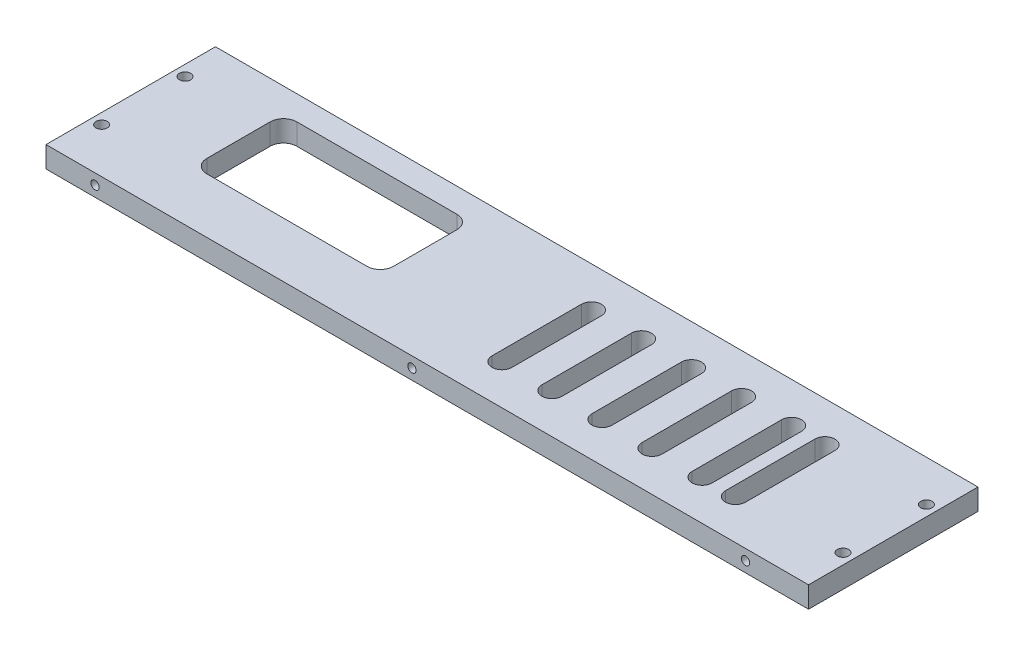
SolidWorks part; units mm, degrees
material "Aleación 6061"
ref_plane "Alzado" through (0, 0, 0) normal (0, 0, 1) x (1, 0, 0)
ref_plane "Planta" through (0, 0, 0) normal (0, 1, 0) x (1, 0, 0)
ref_plane "Vista lateral" through (0, 0, 0) normal (1, 0, 0) x (0, 0, -1)
sketch "Croquis1" plane through (0, 0, 0) normal (0, 1, 0) x (1, 0, 0)
  line L1 (-139.7, -12.7) -> (88.9, -12.7)
  line L2 (-139.7, -12.7) -> (-139.7, -63.5)
  line L3 (-139.7, -63.5) -> (88.9, -63.5)
  line L4 (88.9, -12.7) -> (88.9, -63.5)
  dimension "D1" = 139.7
  dimension "D2" = 12.7
  dimension "D3" = 88.9
  dimension "D4" = 12.7
  dimension "D5" = 139.7
  dimension "D6" = 63.5
  dimension "D7" = 88.9
  dimension "D8" = 63.5
extrude "Pared_-Y_1-4in" add sketch "Croquis1" along normal blind 6.35 from offset 101.6
sketch "Croquis2" plane through (0, 0, 0) normal (0, 0, 1) x (1, 0, 0)
  circle A0 centre (-125, -98.425) radius 1.25
  circle A1 centre (-30, -98.425) radius 1.25
  circle A2 centre (70, -98.425) radius 1.25
  dimension "D1" = 2.5
  dimension "D2" = 2.5
  dimension "D3" = 2.5
  dimension "D4" = 125
  dimension "D5" = 98.425
  dimension "D6" = 30
  dimension "D7" = 98.425
  dimension "D8" = 70
  dimension "D9" = 98.425
extrude "Rosca_M3_inferior" cut sketch "Croquis2" along normal blind 10 from offset 12.7
sketch "Croquis3" plane through (0, 0, 0) normal (0, 0, 1) x (1, 0, 0)
  circle A0 centre (-125, -98.425) radius 1.25
  circle A1 centre (-30, -98.425) radius 1.25
  circle A2 centre (70, -98.425) radius 1.25
  dimension "D1" = 2.5
  dimension "D2" = 2.5
  dimension "D3" = 2.5
  dimension "D4" = 125
  dimension "D5" = 98.425
  dimension "D6" = 30
  dimension "D7" = 98.425
  dimension "D8" = 70
  dimension "D9" = 98.425
extrude "Rosca_M3_superior" cut sketch "Croquis3" along normal blind 10 from offset 53.5
sketch "Croquis4" plane through (0, 0, 0) normal (0, 1, 0) x (1, 0, 0)
  circle A0 centre (-136.525, -25) radius 1.7
  circle A1 centre (-136.525, -50) radius 1.7
  circle A2 centre (85.725, -25) radius 1.7
  circle A3 centre (85.725, -50) radius 1.7
  dimension "D1" = 3.4
  dimension "D2" = 3.4
  dimension "D3" = 3.4
  dimension "D4" = 3.4
  dimension "D5" = 136.525
  dimension "D6" = 25
  dimension "D7" = 136.525
  dimension "D8" = 50
  dimension "D9" = 85.725
  dimension "D10" = 25
  dimension "D11" = 85.725
  dimension "D12" = 50
extrude "Barrenos_M3_esquinas" cut sketch "Croquis4" along normal blind 6.35 from offset 101.6
sketch "Croquis5" plane through (0, 0, 0) normal (0, 1, 0) x (1, 0, 0)
  circle A0 centre (-136.525, -25) radius 2.9
  circle A1 centre (-136.525, -50) radius 2.9
  circle A2 centre (85.725, -25) radius 2.9
  circle A3 centre (85.725, -50) radius 2.9
  dimension "D1" = 5.8
  dimension "D2" = 5.8
  dimension "D3" = 5.8
  dimension "D4" = 5.8
  dimension "D5" = 136.525
  dimension "D6" = 25
  dimension "D7" = 136.525
  dimension "D8" = 50
  dimension "D9" = 85.725
  dimension "D10" = 25
  dimension "D11" = 85.725
  dimension "D12" = 50
extrude "Refrentado_M3_esquinas" cut sketch "Croquis5" along normal blind 3.2 from offset 101.6
sketch "Croquis6" plane through (0, 0, 0) normal (0, 1, 0) x (1, 0, 0)
  line L0 (-108, -47) -> (-60, -47)
  line L1 (-56, -43) -> (-56, -24)
  line L2 (-60, -20) -> (-108, -20)
  line L3 (-112, -24) -> (-112, -43)
  arc A0 (-60, -47) -> (-56, -43) centre (-60, -43) ccw
  arc A1 (-56, -24) -> (-60, -20) centre (-60, -24) ccw
  arc A2 (-108, -20) -> (-112, -24) centre (-108, -24) ccw
  arc A3 (-112, -43) -> (-108, -47) centre (-108, -43) ccw
  dimension "D1" = 4
  dimension "D2" = 4
  dimension "D3" = 4
  dimension "D4" = 4
  dimension "D5" = 108
  dimension "D6" = 47
  dimension "D7" = 60
  dimension "D8" = 47
  dimension "D9" = 56
  dimension "D10" = 43
  dimension "D11" = 56
  dimension "D12" = 24
  dimension "D13" = 60
  dimension "D14" = 20
  dimension "D15" = 108
  dimension "D16" = 20
  dimension "D17" = 112
  dimension "D18" = 24
  dimension "D19" = 112
  dimension "D20" = 43
extrude "Ventana_puertos_RPi5" cut sketch "Croquis6" along normal blind 6.35 from offset 101.6
sketch "Croquis7" plane through (0, 0, 0) normal (0, 1, 0) x (1, 0, 0)
  line L0 (-12, -24.7) -> (-12, -51.5)
  line L1 (-18, -51.5) -> (-18, -24.7)
  line L2 (3, -24.7) -> (3, -51.5)
  line L3 (-3, -51.5) -> (-3, -24.7)
  line L4 (18, -24.7) -> (18, -51.5)
  line L5 (12, -51.5) -> (12, -24.7)
  line L6 (33, -24.7) -> (33, -51.5)
  line L7 (27, -51.5) -> (27, -24.7)
  line L8 (48, -24.7) -> (48, -51.5)
  line L9 (42, -51.5) -> (42, -24.7)
  line L10 (58, -24.7) -> (58, -51.5)
  line L11 (52, -51.5) -> (52, -24.7)
  arc A0 (-12, -51.5) -> (-18, -51.5) centre (-15, -51.5) cw
  arc A1 (-18, -24.7) -> (-12, -24.7) centre (-15, -24.7) cw
  arc A2 (3, -51.5) -> (-3, -51.5) centre (0, -51.5) cw
  arc A3 (-3, -24.7) -> (3, -24.7) centre (0, -24.7) cw
  arc A4 (18, -51.5) -> (12, -51.5) centre (15, -51.5) cw
  arc A5 (12, -24.7) -> (18, -24.7) centre (15, -24.7) cw
  arc A6 (33, -51.5) -> (27, -51.5) centre (30, -51.5) cw
  arc A7 (27, -24.7) -> (33, -24.7) centre (30, -24.7) cw
  arc A8 (48, -51.5) -> (42, -51.5) centre (45, -51.5) cw
  arc A9 (42, -24.7) -> (48, -24.7) centre (45, -24.7) cw
  arc A10 (58, -51.5) -> (52, -51.5) centre (55, -51.5) cw
  arc A11 (52, -24.7) -> (58, -24.7) centre (55, -24.7) cw
  dimension "D1" = 3
  dimension "D2" = 3
  dimension "D3" = 3
  dimension "D4" = 3
  dimension "D5" = 3
  dimension "D6" = 3
  dimension "D7" = 3
  dimension "D8" = 3
  dimension "D9" = 3
  dimension "D10" = 3
  dimension "D11" = 3
  dimension "D12" = 3
  dimension "D13" = 12
  dimension "D14" = 24.7
  dimension "D15" = 12
  dimension "D16" = 51.5
  dimension "D17" = 18
  dimension "D18" = 51.5
  dimension "D19" = 18
  dimension "D20" = 24.7
  dimension "D21" = 3
  dimension "D22" = 24.7
  dimension "D23" = 3
  dimension "D24" = 51.5
  dimension "D25" = 3
  dimension "D26" = 51.5
  dimension "D27" = 3
  dimension "D28" = 24.7
  dimension "D29" = 18
  dimension "D30" = 24.7
  dimension "D31" = 18
  dimension "D32" = 51.5
  dimension "D33" = 12
  dimension "D34" = 51.5
  dimension "D35" = 12
  dimension "D36" = 24.7
  dimension "D37" = 33
  dimension "D38" = 24.7
  dimension "D39" = 33
  dimension "D40" = 51.5
  dimension "D41" = 27
  dimension "D42" = 51.5
  dimension "D43" = 27
  dimension "D44" = 24.7
  dimension "D45" = 48
  dimension "D46" = 24.7
  dimension "D47" = 48
  dimension "D48" = 51.5
  dimension "D49" = 42
  dimension "D50" = 51.5
  dimension "D51" = 42
  dimension "D52" = 24.7
  dimension "D53" = 58
  dimension "D54" = 24.7
  dimension "D55" = 58
  dimension "D56" = 51.5
  dimension "D57" = 52
  dimension "D58" = 51.5
  dimension "D59" = 52
  dimension "D60" = 24.7
extrude "Ranuras_ventilacion" cut sketch "Croquis7" along normal blind 6.35 from offset 101.6
